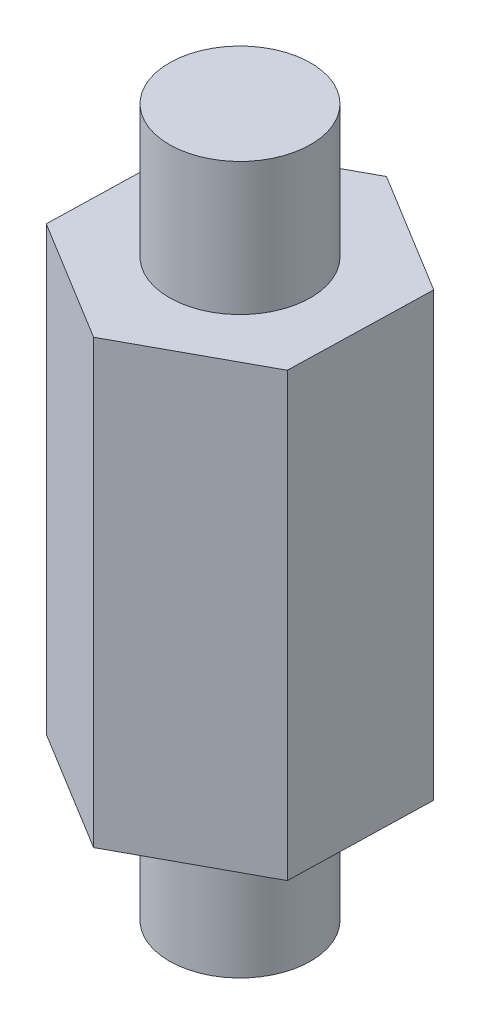
SolidWorks part; units mm, degrees
ref_plane "前视基准面" through (0, 0, 0) normal (0, 0, 1) x (1, 0, 0)
ref_plane "上视基准面" through (0, 0, 0) normal (0, 1, 0) x (1, 0, 0)
ref_plane "右视基准面" through (0, 0, 0) normal (1, 0, 0) x (0, 0, -1)
sketch "草图1" plane through (0, 0, 0) normal (0, 1, 0) x (1, 0, 0)
  circle A0 centre (0, 0) radius 1.6
  dimension "D1" = 3.2
extrude "凸台-拉伸1" add sketch "草图1" along normal blind 3
sketch "草图2" plane through (0, 3, 0) normal (0, 1, 0) x (1, 0, 0)
  line L1 (2.757, -1.6865) -> (2.839, 1.5444)
  line L2 (2.839, 1.5444) -> (0.082, 3.2309)
  line L3 (0.082, 3.2309) -> (-2.757, 1.6865)
  line L4 (-2.757, 1.6865) -> (-2.839, -1.5444)
  line L5 (-2.839, -1.5444) -> (-0.082, -3.2309)
  line L6 (-0.082, -3.2309) -> (2.757, -1.6865)
  circle A0 centre (0, 0) radius 2.7989 construction
extrude "凸台-拉伸2" add sketch "草图2" along normal blind 10
sketch "草图3" plane through (0, 13, 0) normal (0, 1, 0) x (1, 0, 0)
  circle A0 centre (0, 0) radius 1.6
  dimension "D1" = 3.2
extrude "凸台-拉伸3" add sketch "草图3" along normal blind 3
